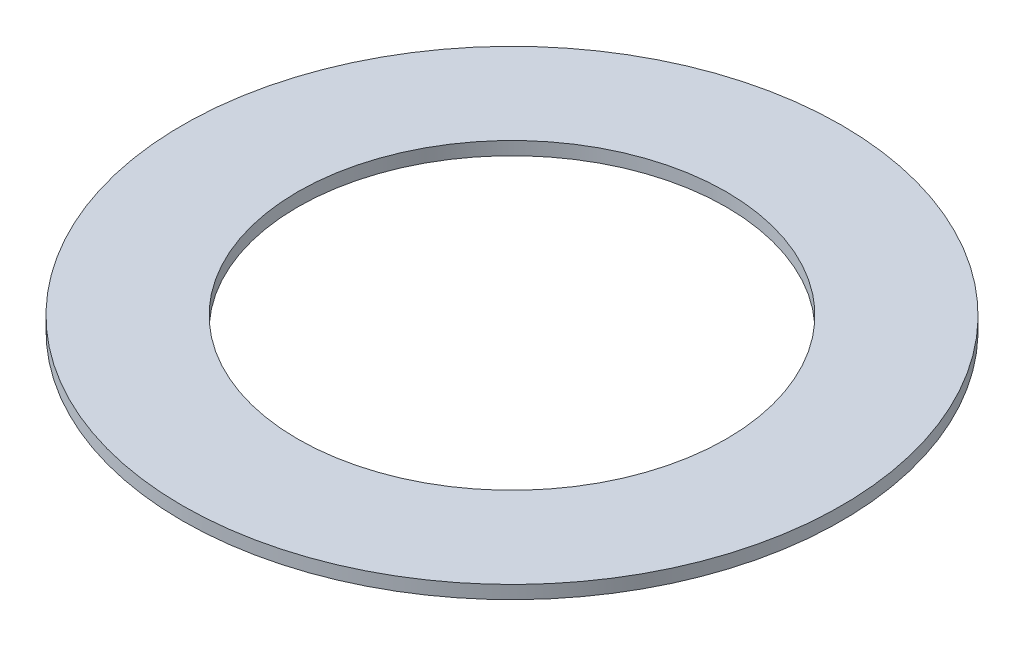
SolidWorks part; units mm, degrees
ref_plane "Front Plane" through (0, 0, 0) normal (0, 0, 1) x (1, 0, 0)
ref_plane "Top Plane" through (0, 0, 0) normal (0, 1, 0) x (1, 0, 0)
ref_plane "Right Plane" through (0, 0, 0) normal (1, 0, 0) x (0, 0, -1)
sketch "Sketch1" plane through (0, 0, 0) normal (0, 1, 0) x (1, 0, 0)
  circle A0 centre (0, 0) radius 6.5
  circle A1 centre (0, 0) radius 10
extrude "Boss-Extrude1" add sketch "Sketch1" along normal blind 0.4
